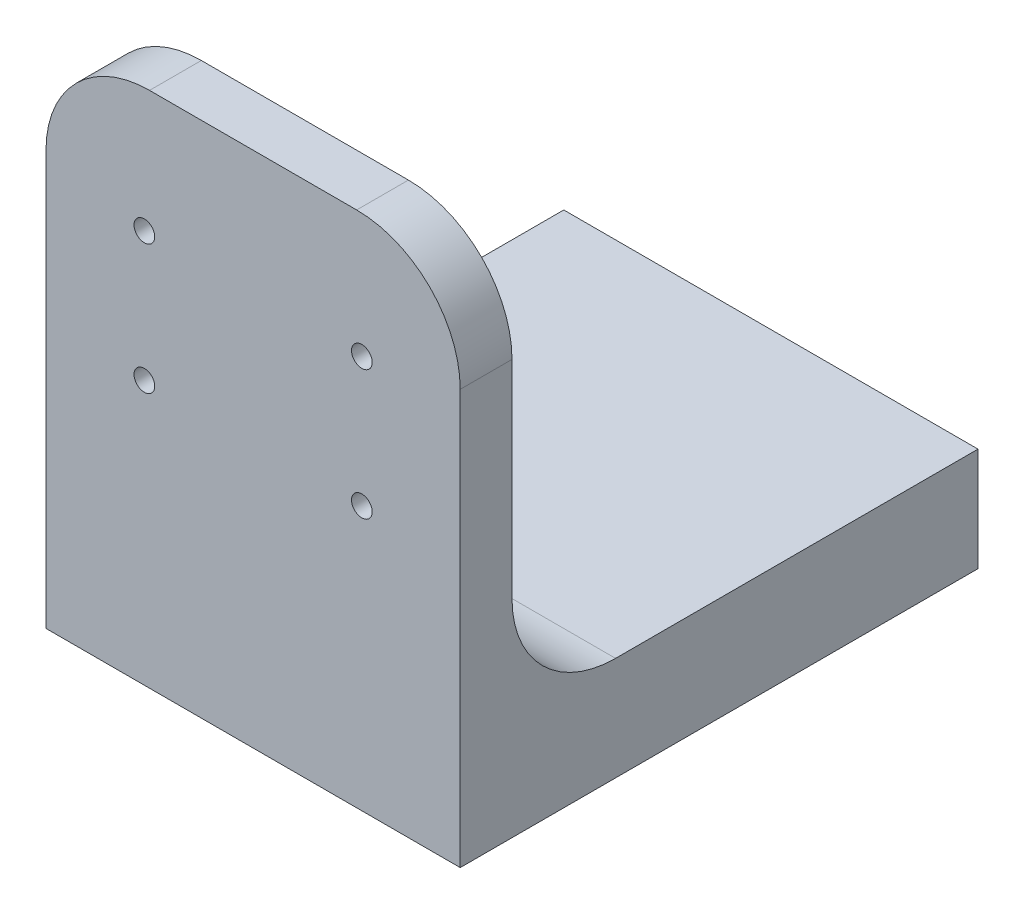
SolidWorks part; units mm, degrees
ref_plane "Front Plane" through (0, 0, 0) normal (0, 0, 1) x (1, 0, 0)
ref_plane "Top Plane" through (0, 0, 0) normal (0, 1, 0) x (1, 0, 0)
ref_plane "Right Plane" through (0, 0, 0) normal (1, 0, 0) x (0, 0, -1)
sketch "Sketch1" plane through (0, 0, 0) normal (0, 1, 0) x (1, 0, 0)
  line L1 (-20, -25) -> (20, -25)
  line L2 (-20, -25) -> (-20, 25)
  line L3 (-20, 25) -> (20, 25)
  line L4 (20, -25) -> (20, 25)
  line L5 (-20, -25) -> (20, 25) construction
  line L6 (-20, 25) -> (20, -25) construction
  point P0 (0, 0)
  dimension "D1" = 50
  dimension "D2" = 40
extrude "Boss-Extrude1" add sketch "Sketch1" along normal blind 10
sketch "Sketch2" plane through (0, 10, 0) normal (0, 1, 0) x (1, 0, 0)
  line L0 (20, -25) -> (20, 25) construction
  line L1 (-20, -25) -> (20, -25)
  line L2 (-20, -25) -> (-20, -20)
  line L3 (-20, -20) -> (20, -20)
  line L4 (20, -25) -> (20, -20)
  dimension "D1" = 5
extrude "Boss-Extrude2" add sketch "Sketch2" along normal blind 40
sketch "Sketch3" plane through (0, 0, 25) normal (0, 0, 1) x (1, 0, 0)
  circle A0 centre (10.5, 25.5) radius 1 construction
  circle A1 centre (-10.5, 25.5) radius 1 construction
  circle A2 centre (10.5, 38) radius 1 construction
  circle A3 centre (-10.5, 38) radius 1 construction
  circle A4 centre (10.5, 25.5) radius 1
  circle A5 centre (-10.5, 25.5) radius 1
  circle A6 centre (10.5, 38) radius 1
  circle A7 centre (-10.5, 38) radius 1
hole_wizard "Ø2.0mm Dowel Hole1" positions "Sketch4" profile "Sketch5" hole size "Ø2.0" standard "ANSI Metric" end condition through all
sketch "Sketch4" plane through (0, 0, 25) normal (0, 0, 1) x (1, 0, 0)
  point P0 (-10.5, 38)
  point P3 (10.5, 38)
  point P6 (-10.5, 25.5)
  point P9 (10.5, 25.5)
sketch "Sketch5" plane through (-10.5, 38, 25) normal (1, 0, 0) x (0, -1, 0)
  line L0 (0, 0) -> (0, 50)
  line L1 (0, 50) -> (1, 50)
  line L2 (1, 50) -> (1, 0)
  line L5 (1, 0) -> (0, 0)
  line L11 (0, -6.35) -> (0, 107.95) construction
  dimension "Thru Hole Dia." = 2
  dimension "Thru Hole Depth" = 50
fillet "Fillet1" radius 10 3 edges at (-20, 50, 22.5) (20, 50, 22.5) (0, 10, 20)
